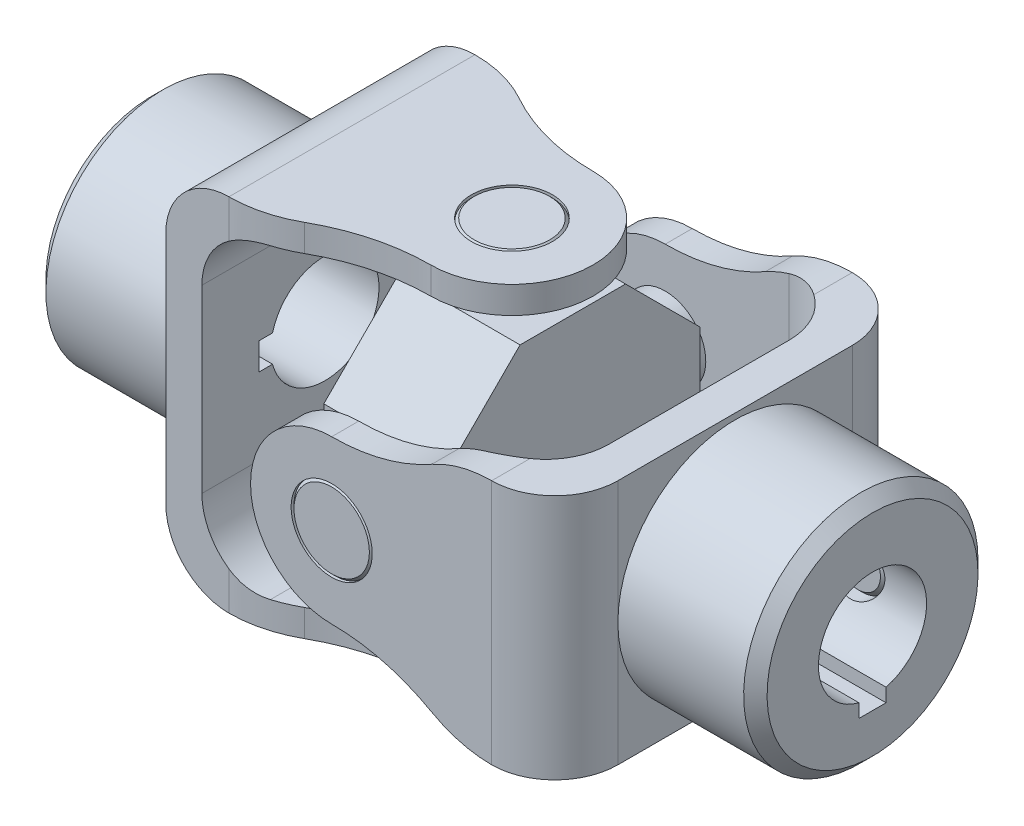
SolidWorks part; units mm, degrees
ref_plane "Front Plane" through (0, 0, 0) normal (0, 0, 1) x (1, 0, 0)
ref_plane "Top Plane" through (0, 0, 0) normal (0, 1, 0) x (1, 0, 0)
ref_plane "Right Plane" through (0, 0, 0) normal (1, 0, 0) x (0, 0, -1)
sketch "Sketch0" plane through (0, 0, 0) normal (0, 1, 0) x (1, 0, 0)
  line L0 (-63.5, 0) -> (63.5, 0) construction
  line L1 (-63.5, 20.6375) -> (-63.5, -20.6375) construction
  line L2 (-32.9406, 9.525) -> (-32.9406, -9.525) construction
  line L3 (-32.9406, 9.525) -> (-23.4156, 0) construction
  line L4 (-23.4156, 0) -> (-32.9406, -9.525) construction
  line L5 (-28.1781, 4.7625) -> (-28.1781, -4.7625) construction
  line L6 (0, 31.75) -> (0, -31.75) construction
  point P7 (-32.9406, 0)
  point P8 (0, 0)
  point P12 (-28.1781, 0)
  dimension "Overall Width" = 63.5
  dimension "Shaft Dia" = 19.05
sketch "Sketch1" plane through (0, 0, 0) normal (0, 1, 0) x (1, 0, 0)
  line L0 (-63.5, 20.6375) -> (-32.9406, 20.6375)
  line L2 (-32.9406, 0) -> (-63.5, 0)
  line L3 (-63.5, 0) -> (-63.5, 20.6375)
  line L4 (-63.5, 20.6375) -> (-63.5, -20.6375) construction
  line L5 (-63.5, 0) -> (63.5, 0) construction
  line L9 (-32.9406, 20.6375) -> (-32.9406, 0)
  line L11 (0, 0) -> (20.6375, 0) construction
  line L14 (0, 31.75) -> (0, 0) construction
  circle A0 centre (0, 0) radius 20.6375 construction
revolve "Revolve1" add sketch "Sketch1" angle 360 about L0
sketch "Sketch30" plane through (0, 0, 0) normal (0, 1, 0) x (1, 0, 0)
  line L0 (-39.2906, 21.6694) -> (-39.2906, -21.6694)
  line L1 (-39.2906, -21.6694) -> (-21.8281, -21.6694)
  line L2 (-39.2906, 21.6694) -> (-21.8281, 21.6694)
  line L3 (0, 14.2875) -> (-25.0022, 14.2875) construction
  line L4 (0, -14.2875) -> (-25.0022, -14.2875) construction
  line L5 (-21.8281, 21.6694) -> (14.2875, 21.6694)
  line L6 (14.2875, 21.6694) -> (14.2875, -21.6694)
  line L7 (-21.8281, -21.6694) -> (14.2875, -21.6694)
  line L8 (0, 31.75) -> (0, -31.75) construction
  line L9 (9.525, 0) -> (14.2875, 0) construction
  circle A0 centre (0, 0) radius 9.525 construction
  arc A2 (0, -14.2875) -> (0, 14.2875) centre (0, 0) ccw construction
  arc A3 (0, 14.2875) -> (-21.8281, 21.6694) centre (0, 50.2512) cw construction
  arc A4 (0, -14.2875) -> (-21.8281, -21.6694) centre (0, -50.2512) ccw construction
  circle A5 centre (0, 0) radius 14.2875 construction
  point P5 (12.388, 3.7874)
  dimension "D2" = 19.05
  dimension "D1" = 43.3388
  dimension "D3" = 4.7625
  dimension "D4" = 6.35
  dimension "D5" = 17.4625
extrude "Boss-Extrude6" add sketch "Sketch30" along normal mid plane 63.5
chamfer "Chamfer1" distance 2.0638 angle 45 1 edges at (-63.5, 0, 20.6375)
sketch "Sketch3" plane through (0, 0, 0) normal (0, 0, 1) x (1, 0, 0)
  line L0 (-63.5, 0) -> (63.5, 0) construction
  line L1 (-32.9406, 0) -> (32.9406, 0) construction
  line L2 (-21.8281, 26.9875) -> (32.9406, 26.9875)
  line L3 (32.9406, 26.9875) -> (32.9406, -26.9875)
  line L4 (-21.8281, -26.9875) -> (32.9406, -26.9875)
  line L5 (-32.9406, 15.875) -> (-32.9406, -15.875)
  line L7 (-39.2906, 31.75) -> (14.2875, 31.75) construction
  line L8 (-39.2906, 31.75) -> (-39.2906, -31.75) construction
  line L9 (-39.2906, 31.75) -> (-28.1781, 31.75)
  line L10 (-39.2906, 31.75) -> (-39.2906, 20.6375)
  line L11 (-39.2906, -31.75) -> (-39.2906, -20.6375)
  line L12 (-39.2906, -31.75) -> (-28.1781, -31.75)
  arc A0 (-39.2906, 20.6375) -> (-28.1781, 31.75) centre (-28.1781, 20.6375) cw
  arc A1 (-32.9406, 15.875) -> (-21.8281, 26.9875) centre (-21.8281, 15.875) cw
  arc A2 (-32.9406, -15.875) -> (-21.8281, -26.9875) centre (-21.8281, -15.875) ccw
  arc A3 (-39.2906, -20.6375) -> (-28.1781, -31.75) centre (-28.1781, -20.6375) ccw
  dimension "D2" = 53.975
  dimension "D1" = 4.7625
  dimension "D4" = 17.4625
extrude "Extrude3" cut sketch "Sketch3" against normal through all and the other way through all
sketch "Sketch2" plane through (0, 0, 0) normal (0, 1, 0) x (1, 0, 0)
  line L0 (-52.3875, 20.6375) -> (-32.9406, 20.6375) construction
  line L1 (-21.8281, -21.6694) -> (-21.8281, -31.75) construction
  line L2 (-21.8281, 21.6694) -> (-21.8281, 31.75) construction
  line L3 (-32.9406, 9.525) -> (-32.9406, -9.525) construction
  line L4 (-63.5, 0) -> (14.2875, 0) construction
  line L6 (20.6375, 31.75) -> (20.6375, -31.75)
  line L8 (0, 14.2875) -> (0, 0) construction
  line L9 (-21.8281, 31.75) -> (20.6375, 31.75)
  line L10 (-32.9406, 20.6375) -> (-32.9406, -14.4138) construction
  line L11 (-39.2906, 21.6694) -> (-21.8281, 21.6694) construction
  line L12 (-21.8281, -31.75) -> (20.6375, -31.75)
  line L13 (-63.5, 20.6375) -> (-32.9406, 20.6375) construction
  line L14 (-28.1781, 21.6694) -> (-21.8281, 31.75)
  line L15 (-63.5, 0) -> (63.5, 0) construction
  line L16 (-21.8281, -31.75) -> (-28.1781, -21.6694)
  line L17 (-39.2906, -21.6694) -> (-21.8281, -21.6694) construction
  arc A0 (0, -14.2875) -> (-21.8281, -21.6694) centre (0, -50.2512) ccw construction
  arc A1 (0, -14.2875) -> (0, 14.2875) centre (0, 0) ccw construction
  arc A2 (-21.8281, 21.6694) -> (0, 14.2875) centre (0, 50.2512) ccw construction
  arc A3 (0, -14.2875) -> (-17.6328, -18.9068) centre (0, -50.2512) ccw
  arc A4 (0, -14.2875) -> (0, 14.2875) centre (0, 0) ccw
  arc A5 (-17.6328, 18.9068) -> (0, 14.2875) centre (0, 50.2512) ccw
  arc A6 (-28.1781, 21.6694) -> (-17.6328, 18.9068) centre (-28.1781, 0.1613) cw
  arc A7 (-28.1781, -21.6694) -> (-17.6328, -18.9068) centre (-28.1781, -0.1613) ccw
extrude "Extrude1" cut sketch "Sketch2" against normal through all and the other way through all
sketch "Sketch4" plane through (-63.5, 0, 0) normal (-1, 0, 0) x (0, 0, 1)
  circle A0 centre (0, 0) radius 9.525
  circle A1 centre (0, 0) radius 9.525 construction
  dimension "Max Bore Dia" = 19.05
extrude "Extrude4" cut sketch "Sketch4" against normal up to vertex (30.5594 mm away) up to point (-32.9406, 0, -9.525)
sketch "Sketch6" plane through (0, 0, 0) normal (0, 1, 0) x (1, 0, 0)
  line L0 (-63.5, 0) -> (63.5, 0) construction
  line L1 (14.2875, 0) -> (7.1437, 0) construction
  line L2 (7.1437, 0) -> (0, 0) construction
  line L3 (14.2875, 21.6694) -> (14.2875, -21.6694) construction
  circle A0 centre (0, 0) radius 7.1437
  dimension "D1" = 14.2875
extrude "Extrude6" cut sketch "Sketch6" against normal through all and the other way through all
sketch "Sketch33" plane through (-63.5, 0, 0) normal (-1, 0, 0) x (0, 0, 1)
  line L0 (0, 0) -> (9.2225, 0) construction
  line L1 (9.2225, 2.3813) -> (11.6038, 2.3813)
  line L2 (9.2225, 2.3813) -> (9.2225, -2.3813)
  line L3 (9.2225, -2.3813) -> (11.6038, -2.3813)
  line L4 (11.6038, 2.3813) -> (11.6038, -2.3813)
  circle A0 centre (0, 0) radius 9.525 construction
  dimension "D1" = 4.7625
  dimension "D2" = 2.3813
extrude "Cut-Extrude1" cut sketch "Sketch33" against normal through all
sketch "Sketch34" plane through (0, 0, 0) normal (0, 1, 0) x (1, 0, 0)
  line L0 (-39.2906, 0) -> (-63.5, 0) construction
  line L2 (-63.5, 18.5737) -> (-63.5, -18.5737) construction
  circle A0 centre (-51.3953, 0) radius 4.7625
  point P7 (-39.2906, 0)
  point P8 (-51.3953, 0)
  dimension "D1" = 9.525
extrude "Cut-Extrude2" cut sketch "Sketch34" against normal through all
ref_plane "Plane1" through (-51.3953, 0, 0) normal (1, 0, 0) x (0, 0, -1)
sketch "Sketch35" plane through (-51.3953, 0, 0) normal (1, 0, 0) x (0, 0, -1)
  line L0 (-3.9688, -9.525) -> (-4.7625, -10.3187)
  line L1 (0, -9.525) -> (-3.9688, -9.525)
  line L2 (0, -9.525) -> (0, -22.225) construction
  line L3 (0, -22.225) -> (-3.9687, -22.225)
  line L4 (-4.7625, -10.3187) -> (-4.7625, -21.4313)
  line L5 (-3.9687, -22.225) -> (-4.7625, -21.4313)
  line L6 (0, -9.525) -> (0, -22.225)
  arc A0 (-9.2225, -2.3813) -> (-9.2225, 2.3813) centre (0, 0) ccw construction
  point P1 (-4.7625, -22.225)
  point P3 (-4.7625, -9.525)
  dimension "D1" = 12.7
  dimension "D2" = 9.525
  dimension "D3" = 0.7938
  dimension "D4" = 45
  dimension "D5" = 0.7938
  dimension "D6" = 45
revolve "Revolve2" add sketch "Sketch35" angle 360 about L2
sketch "Sketch36" plane through (0, -22.225, 0) normal (0, -1, 0) x (1, 0, 0)
  line L1 (-51.3953, -2.7496) -> (-49.0141, -1.3748)
  line L2 (-49.0141, -1.3748) -> (-49.0141, 1.3748)
  line L3 (-49.0141, 1.3748) -> (-51.3953, 2.7496)
  line L4 (-51.3953, 2.7496) -> (-53.7766, 1.3748)
  line L5 (-53.7766, 1.3748) -> (-53.7766, -1.3748)
  line L6 (-53.7766, -1.3748) -> (-51.3953, -2.7496)
  circle A0 centre (-51.3953, 0) radius 2.3812 construction
  dimension "D1" = 4.7625
extrude "Cut-Extrude3" cut sketch "Sketch36" against normal blind 3.302
sketch "Sketch37" plane through (0, -22.225, 0) normal (0, -1, 0) x (1, 0, 0)
  circle A0 centre (-51.3953, 0) radius 2.7496
  circle A1 centre (-51.3953, 0) radius 3.9687 construction
extrude "Cut-Extrude4" cut sketch "Sketch37" against normal through all draft 45
mirror "Mirror1" about plane through (0, 0, 0) normal (1, 0, 0) of bodies 163 109 122
move or copy body "Body-Move/Copy1" bodies to move or copy 110 copy no rotation origin (0, 0, 0) rotation axis (1, 0, 0) rotation angle 90
sketch "Sketch18" plane through (0, 0, 0) normal (0, 1, 0) x (1, 0, 0)
  line L8 (0, 0) -> (63.5, 0) construction
  line L10 (-32.9406, 9.525) -> (-63.5, 9.525)
  line L12 (-32.9406, 9.525) -> (-32.9406, -9.525)
  line L13 (-32.9406, -9.525) -> (-63.5, -9.525)
  line L14 (-63.5, 20.6375) -> (-63.5, -20.6375) construction
  line L15 (0, 0) -> (0, 21.9558) construction
  line L16 (32.9406, -9.525) -> (63.5, -9.525)
  line L17 (32.9406, 9.525) -> (32.9406, -9.525)
  line L18 (32.9406, 9.525) -> (63.5, 9.525)
sketch "Sketch10" plane through (0, 0, 0) normal (0, 0, 1) x (1, 0, 0)
  circle A0 centre (0, 0) radius 7.1437 construction
  circle A1 centre (0, 0) radius 7.1437
  dimension "D1" = 14.2875
extrude "Extrude10" add sketch "Sketch10" along normal up to surface and the other way up to surface separate body up to face at (0, -7.1438, 31.75) other way up to face at (0, -7.1437, -31.75)
sketch "Sketch31" plane through (0, 0, 0) normal (0, 1, 0) x (1, 0, 0)
  circle A0 centre (0, 0) radius 7.1437 construction
  circle A1 centre (0, 0) radius 7.1437
extrude "Boss-Extrude7" add sketch "Sketch31" against normal up to surface and the other way up to surface separate body up to face at (0, -31.75, 7.1437) other way up to face at (0, 31.75, 7.1437)
sketch "Sketch32" plane through (0, 0, 0) normal (1, 0, 0) x (0, 0, -1)
  line L11 (9.2869, -22.4205) -> (22.4205, -9.2869)
  line L12 (22.4205, -9.2869) -> (22.4205, 9.2869)
  line L13 (22.4205, 9.2869) -> (9.2869, 22.4205)
  line L14 (-14.1457, -7.1438) -> (-31.75, -7.1438) construction
  line L15 (-31.75, 7.1437) -> (-31.75, -7.1438) construction
  line L16 (9.2869, 22.4205) -> (-9.2869, 22.4205)
  line L17 (-9.2869, 22.4205) -> (-22.4205, 9.2869)
  line L18 (-22.4205, 9.2869) -> (-22.4205, -9.2869)
  line L19 (-22.4205, -9.2869) -> (-9.2869, -22.4205)
  line L20 (-9.2869, -22.4205) -> (9.2869, -22.4205)
  circle A0 centre (0, 0) radius 22.4205 construction
  dimension "D2" = 18.5737
extrude "Boss-Extrude8" add sketch "Sketch32" along normal mid plane 21.4312
chamfer "Chamfer2" distance 0.508 angle 45 4 edges at (0, -31.75, -7.1437) (0, 31.75, -7.1437) (0, 7.1437, 31.75) (0, 7.1437, -31.75)
move or copy body "Body-Move/Copy2" [suppressed] bodies to move or copy 111 copy no rotation origin (0, 0, 0) rotation axis (0, 0, -1) rotation angle 45
equation "\"D2@Sketch3\" = \"D1@Sketch3\" / 4"
equation "\"D1@Chamfer1\" = \"OD@Sketch0\"/20"
equation "\"D2@Sketch3\" = \"Overall Width@Sketch0\"*.85"
equation "\"D1@Sketch30\" = \"OD@Sketch0\"*1.05"
equation "\"D1@Boss-Extrude6\" = \"Overall Width@Sketch0\""
equation "\"D5@Sketch30\" = \"D4@Sketch3\""
equation "\"D2@Sketch32\" = \"D1@Sketch10\"*1.3"
equation "\"D1@Boss-Extrude8\" = \"D1@Sketch10\"*1.5"
